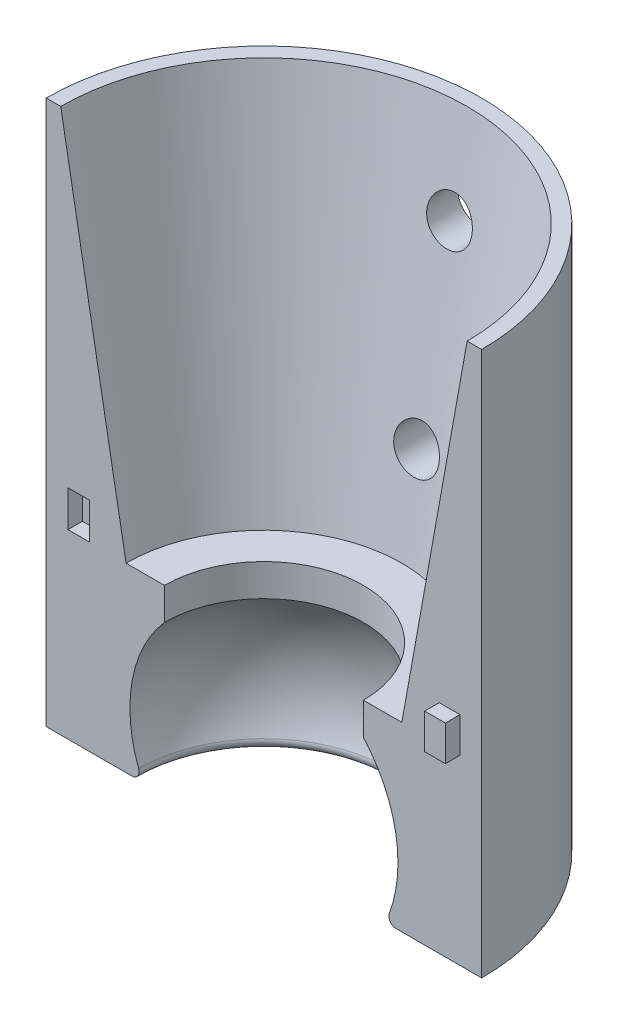
SolidWorks part; units mm, degrees
ref_plane "Front Plane" through (0, 0, 0) normal (0, 0, 1) x (1, 0, 0)
ref_plane "Top Plane" through (0, 0, 0) normal (0, 1, 0) x (1, 0, 0)
ref_plane "Right Plane" through (0, 0, 0) normal (1, 0, 0) x (0, 0, -1)
sketch "Sketch3" plane through (0, 0, 0) normal (0, 0, 1) x (1, 0, 0)
  line L2 (-9.1279, 13.193) -> (-9.1279, -24.7921)
  line L4 (-9.1279, -13.7995) -> (-39.1279, -13.7995)
  line L5 (-9.1279, -13.7995) -> (-9.1279, 61.2005)
  line L6 (-9.1279, 61.2005) -> (-39.1279, 61.2005)
  line L7 (-39.1279, -13.7995) -> (-39.1279, 61.2005)
  line L8 (-22.8384, 11.2005) -> (-9.1279, 11.2005)
  line L9 (-22.8384, 11.2005) -> (-22.8384, 6.7758)
  line L10 (-9.1279, 95.8585) -> (-9.1279, -91.8555) construction
  line L11 (-22.8384, 11.2005) -> (-28.1279, 11.2005)
  line L12 (-28.1279, 11.2005) -> (-37.1279, 61.2005)
  arc A0 (-9.1279, 13.193) -> (-9.1279, -24.7921) centre (-8.5955, -5.7995) ccw
  dimension "D5" = 19
  dimension "D1" = 30
  dimension "D2" = 8
  dimension "D3" = 30
  dimension "D4" = 17
  dimension "D6" = 28
  dimension "D7" = 19
  dimension "D8" = 50
revolve "Revolve8" add sketch "Sketch3" angle 180 about L10
sketch "Sketch5" plane through (0, 0, 0) normal (0, 0, 1) x (1, 0, 0)
  line L0 (20.8721, -13.7995) -> (20.8721, 61.2005) construction
  line L1 (15.0221, 16.1255) -> (17.8721, 16.1255)
  line L2 (15.0221, 16.1255) -> (15.0221, 11.2755)
  line L3 (15.0221, 11.2755) -> (17.8721, 11.2755)
  line L4 (17.8721, 16.1255) -> (17.8721, 11.2755)
  line L5 (7.5735, -13.7995) -> (20.8721, -13.7995) construction
  line L6 (17.8721, 13.7005) -> (20.8721, 13.7005) construction
  line L7 (16.4471, 16.1255) -> (16.4471, -13.7995) construction
  line L8 (16.4471, 13.7005) -> (20.8721, 13.7005) construction
  point P13 (16.4471, 13.7005)
  dimension "D2" = 3
  dimension "D3" = 4.85
  dimension "D4" = 2.85
  dimension "D5" = 4.425
  dimension "D6" = 3
extrude "Boss-Extrude1" add sketch "Sketch5" along normal blind 2
sketch "Sketch6" plane through (0, 0, 0) normal (0, 0, 1) x (1, 0, 0)
  line L0 (-25.8292, -13.7995) -> (-39.1279, -13.7995) construction
  line L1 (-36.1279, 16.2005) -> (-33.1279, 16.2005)
  line L2 (-36.1279, 16.2005) -> (-36.1279, 11.2005)
  line L3 (-36.1279, 11.2005) -> (-33.1279, 11.2005)
  line L4 (-33.1279, 16.2005) -> (-33.1279, 11.2005)
  line L5 (-39.1279, -13.7995) -> (-39.1279, 61.2005) construction
  line L6 (-34.6279, 16.2005) -> (-34.6279, -13.7995) construction
  dimension "D1" = 25
  dimension "D2" = 5
  dimension "D3" = 3
  dimension "D4" = 3
extrude "Cut-Extrude1" cut sketch "Sketch6" against normal blind 2
fillet "Fillet1" radius 1 1 edges at (-9.1279, -13.7995, -16.7013)
sketch "Sketch7" plane through (0, 0, 0) normal (0, 0, 1) x (1, 0, 0)
  line L0 (-9.1279, 11.2005) -> (-9.1279, 36.2005) construction
  line L1 (4.5827, 11.2005) -> (-22.8384, 11.2005) construction
  line L2 (-9.1279, 36.2005) -> (-9.1279, 61.2005) construction
  line L3 (18.8721, 61.2005) -> (-37.1279, 61.2005) construction
  circle A0 centre (-9.1279, 23.7005) radius 3.1
  circle A1 centre (-9.1279, 48.7005) radius 3.1
  dimension "D2" = 6.2
  dimension "D3" = 6.2
  dimension "D1" = 25
extrude "Cut-Extrude2" cut sketch "Sketch7" against normal blind 40
